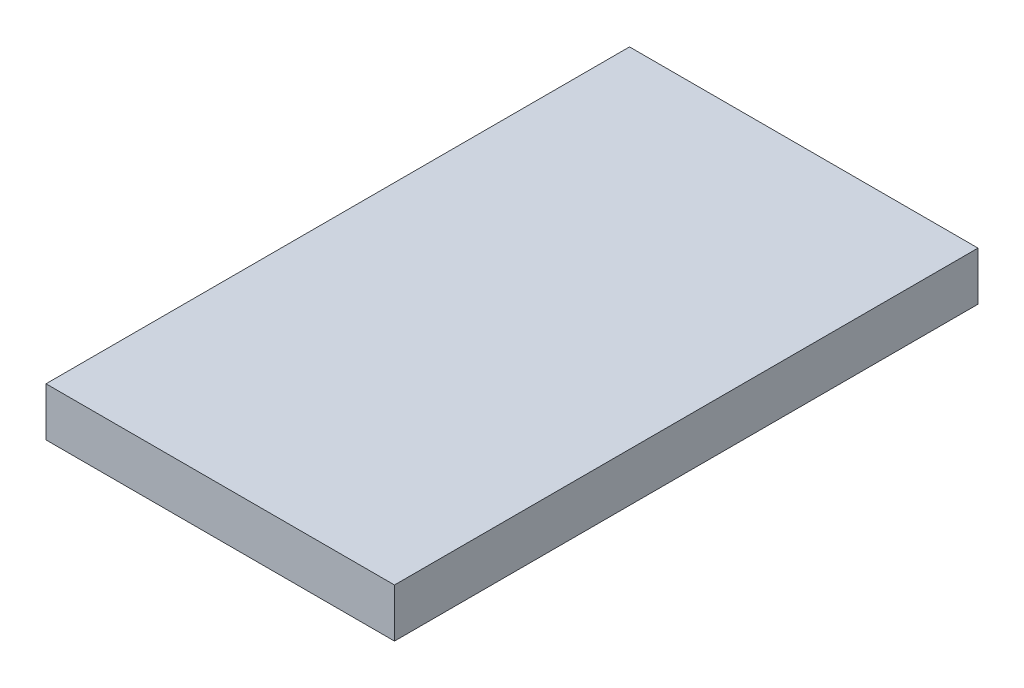
SolidWorks part; units mm, degrees
ref_plane "Front Plane" through (0, 0, 0) normal (0, 0, 1) x (1, 0, 0)
ref_plane "Top Plane" through (0, 0, 0) normal (0, 1, 0) x (1, 0, 0)
ref_plane "Right Plane" through (0, 0, 0) normal (1, 0, 0) x (0, 0, -1)
sketch "Sketch1" plane through (0, 0, 0) normal (0, 1, 0) x (1, 0, 0)
  line L1 (-21.5, 36) -> (21.5, 36)
  line L2 (-21.5, 36) -> (-21.5, -36)
  line L3 (-21.5, -36) -> (21.5, -36)
  line L4 (21.5, 36) -> (21.5, -36)
  line L5 (-21.5, 36) -> (21.5, -36) construction
  line L6 (-21.5, -36) -> (21.5, 36) construction
  point P0 (0, 0)
  dimension "D1" = 43
  dimension "D2" = 72
extrude "Boss-Extrude1" add sketch "Sketch1" along normal blind 6
sketch "Sketch2" plane through (0, 6, 0) normal (0, 1, 0) x (1, 0, 0)
  line L0 (0, -25.3285) -> (0, 22.608) construction
  line L1 (0, 0) -> (28.0008, 0) construction
  circle A0 centre (15, -33) radius 1.5
  circle A1 centre (-15, -33) radius 1.5
  circle A2 centre (-15, 33) radius 1.5
  circle A3 centre (15, 33) radius 1.5
  dimension "D1" = 3
  dimension "D2" = 3
